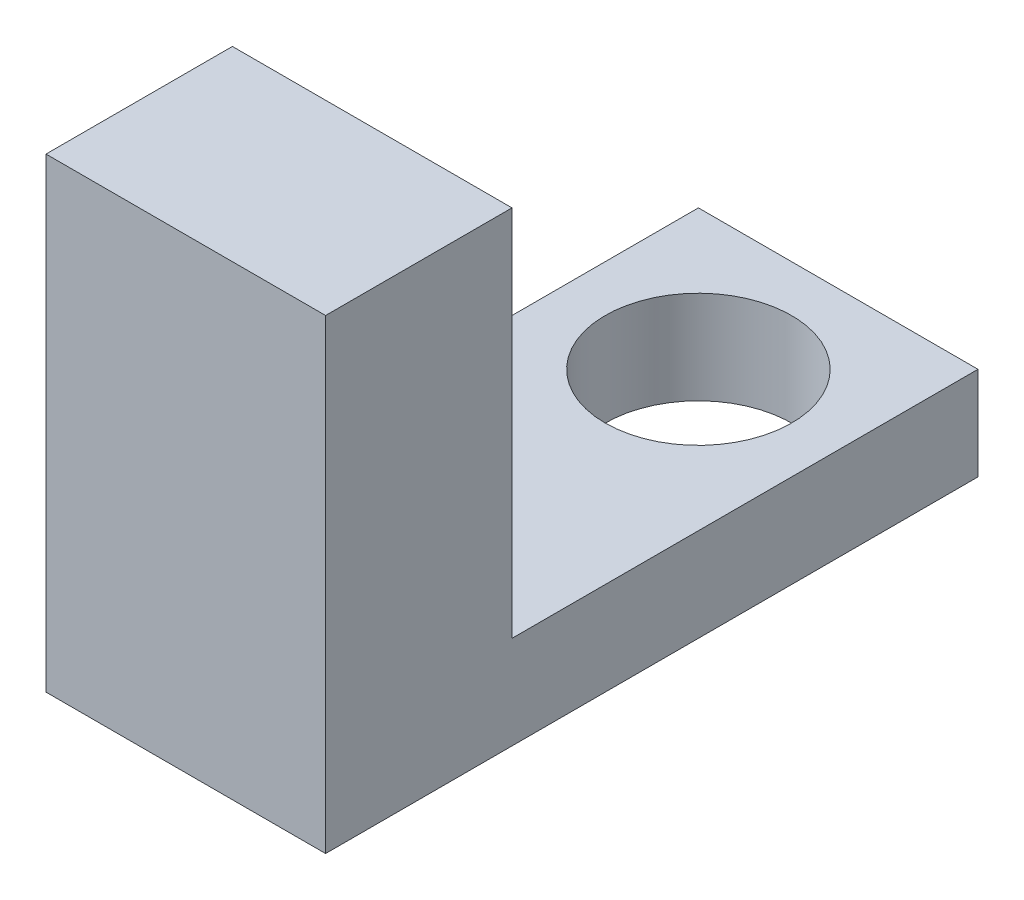
SolidWorks part; units mm, degrees
ref_plane "Front Plane" through (0, 0, 0) normal (0, 0, 1) x (1, 0, 0)
ref_plane "Top Plane" through (0, 0, 0) normal (0, 1, 0) x (1, 0, 0)
ref_plane "Right Plane" through (0, 0, 0) normal (1, 0, 0) x (0, 0, -1)
sketch "Sketch1" plane through (0, 0, 0) normal (1, 0, 0) x (0, 0, -1)
  line L0 (0, 40) -> (0, 0)
  line L1 (0, 0) -> (50, 0)
  line L2 (50, 0) -> (50, -10)
  line L3 (50, -10) -> (-20, -10)
  line L4 (-20, -10) -> (-20, 40)
  line L5 (-20, 40) -> (0, 40)
  dimension "D1" = 10
  dimension "D2" = 50
  dimension "D3" = 70
  dimension "D4" = 50
extrude "Boss-Extrude1" add sketch "Sketch1" along normal blind 30
sketch "Sketch2" plane through (0, 0, 0) normal (0, 1, 0) x (1, 0, 0)
  line L0 (30, 50) -> (0, 50) construction
  line L1 (30, 50) -> (30, 0) construction
  circle A0 centre (15, 35) radius 10
  dimension "D1" = 20
  dimension "D2" = 15
  dimension "D3" = 15
extrude "Cut-Extrude1" cut sketch "Sketch2" against normal blind 10
